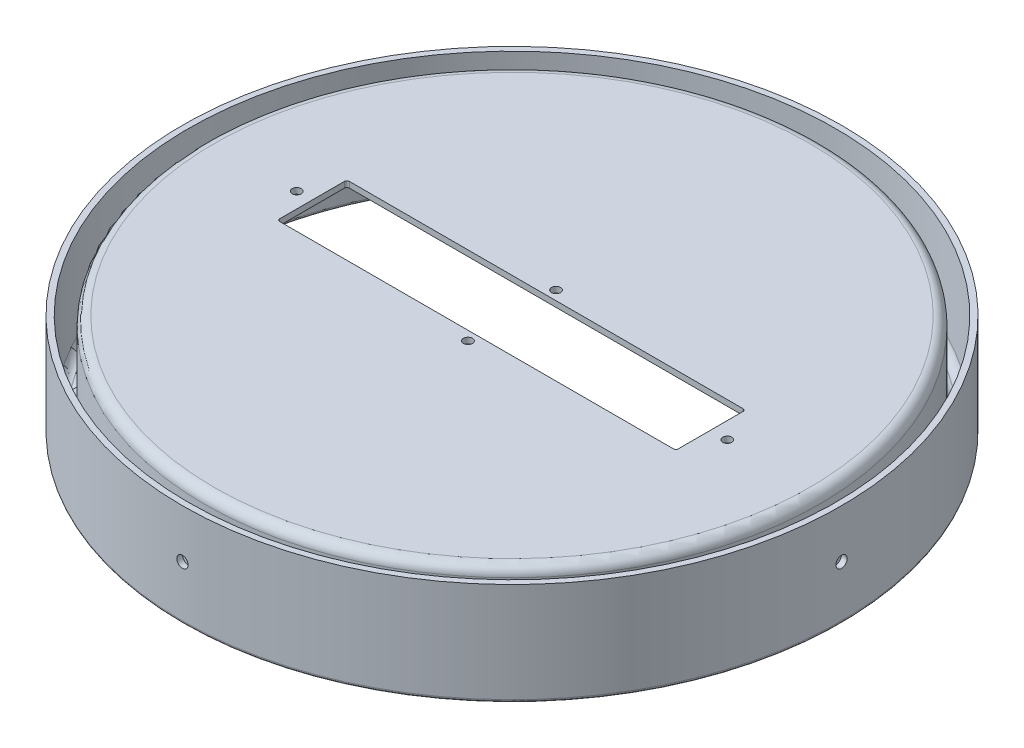
SolidWorks part; units mm, degrees
ref_plane "Piano frontale" through (0, 0, 0) normal (0, 0, 1) x (1, 0, 0)
ref_plane "Piano superiore" through (0, 0, 0) normal (0, 1, 0) x (1, 0, 0)
ref_plane "Piano destro" through (0, 0, 0) normal (1, 0, 0) x (0, 0, -1)
sketch "Schizzo1" plane through (0, 0, 0) normal (0, 0, 1) x (1, 0, 0)
  line L0 (0, 0) -> (-92, 0)
  line L1 (-95, -3) -> (-95, -27.55)
  line L2 (-97.45, -30) -> (-97.55, -30)
  line L3 (-100, -27.55) -> (-100, 0)
  line L4 (0, -1.8) -> (-92, -1.8)
  line L5 (-93.2, -3) -> (-93.2, -30.8)
  line L6 (-94.2, -31.8) -> (-100.8, -31.8)
  line L7 (-101.8, -30.8) -> (-101.8, 0)
  line L8 (-100, 0) -> (-101.8, 0)
  line L9 (-93.2, -31.8) -> (-101.8, -31.8) construction
  line L10 (-101.8, -31.8) -> (-101.8, 0) construction
  line L11 (-93.2, -3) -> (-93.2, -31.8) construction
  line L12 (-95, -3) -> (-95, -30) construction
  line L13 (-95, -30) -> (-100, -30) construction
  line L14 (-100, -30) -> (-100, 0) construction
  line L15 (0, 0) -> (0, -1.8)
  arc A0 (-92, 0) -> (-95, -3) centre (-92, -3) ccw
  arc A1 (-92, -1.8) -> (-93.2, -3) centre (-92, -3) ccw
  arc A2 (-100.8, -31.8) -> (-101.8, -30.8) centre (-100.8, -30.8) cw
  arc A3 (-93.2, -30.8) -> (-94.2, -31.8) centre (-94.2, -30.8) cw
  arc A6 (-97.45, -30) -> (-95, -27.55) centre (-97.45, -27.55) ccw
  arc A7 (-97.55, -30) -> (-100, -27.55) centre (-97.55, -27.55) cw
  point P8 (-95, 0)
  dimension "D2" = 3
  dimension "D4" = 1
  dimension "D5" = 2.45
  dimension "D1" = 95
  dimension "D3" = 1.8
revolve "Rivoluzione1" add sketch "Schizzo1" angle 360 about L15
sketch "Schizzo2" plane through (0, 0, 0) normal (1, 0, 0) x (0, 0, -1)
  line L0 (0, 0) -> (0, -15) construction
  circle A0 centre (0, -15) radius 1.75
  dimension "D2" = 3.5
  dimension "D1" = 15
extrude "Taglio-Estrusione1" cut sketch "Schizzo2" against normal through all and the other way through all
pattern_circular "RipetizioneCircolare1" count 2 every 90 about axis through (0, -30.8, 0) along (0, 1, 0) of "Taglio-Estrusione1"
sketch "Schizzo3" plane through (0, 0, 0) normal (0, 1, 0) x (1, 0, 0)
  line L5 (-61, 10.75) -> (60.6125, 10.75)
  line L6 (61.3625, 10) -> (61.3625, -10)
  line L7 (-61, -10.75) -> (60.6125, -10.75)
  line L8 (-61.75, 10) -> (-61.75, -10)
  arc A0 (-61, -10.75) -> (-61.75, -10) centre (-61, -10) cw
  arc A1 (-61, 10.75) -> (-61.75, 10) centre (-61, 10) ccw
  arc A2 (61.3625, -10) -> (60.6125, -10.75) centre (60.6125, -10) cw
  arc A3 (60.6125, 10.75) -> (61.3625, 10) centre (60.6125, 10) cw
  dimension "D1" = 0.75
extrude "Taglio-Estrusione2" cut sketch "Schizzo3" against normal blind 8.5
extrude "Taglio-Estrusione3" cut sketch "Schizzo4" against normal blind 10
sketch "Schizzo4" plane through (-0.7694, 2, -203.6) normal (0, 1, 0) x (1, 0, 0)
  line L0 (0.7694, -203.6) -> (19.6422, -203.6) construction
  circle A0 centre (0.7694, -187.4976) radius 2.5 construction
  circle A1 centre (0.7694, -189.9976) radius 1.4
  circle A2 centre (0.7694, -219.7024) radius 2.5 construction
  circle A3 centre (0.7694, -217.2024) radius 1.4
extrude "Taglio-Estrusione4" cut sketch "Schizzo5" against normal blind 10
sketch "Schizzo5" plane through (-0.7694, 2, -203.6) normal (0, 1, 0) x (1, 0, 0)
  line L0 (-68.2306, -203.6) -> (0.7694, -203.6) construction
  line L2 (0.7694, -203.6) -> (0.7694, -211.5418) construction
  circle A0 centre (-68.2306, -203.6) radius 2.5 construction
  circle A1 centre (-65.7306, -203.6) radius 1.4
  circle A2 centre (69.7694, -203.6) radius 2.5 construction
  circle A3 centre (67.2694, -203.6) radius 1.4
